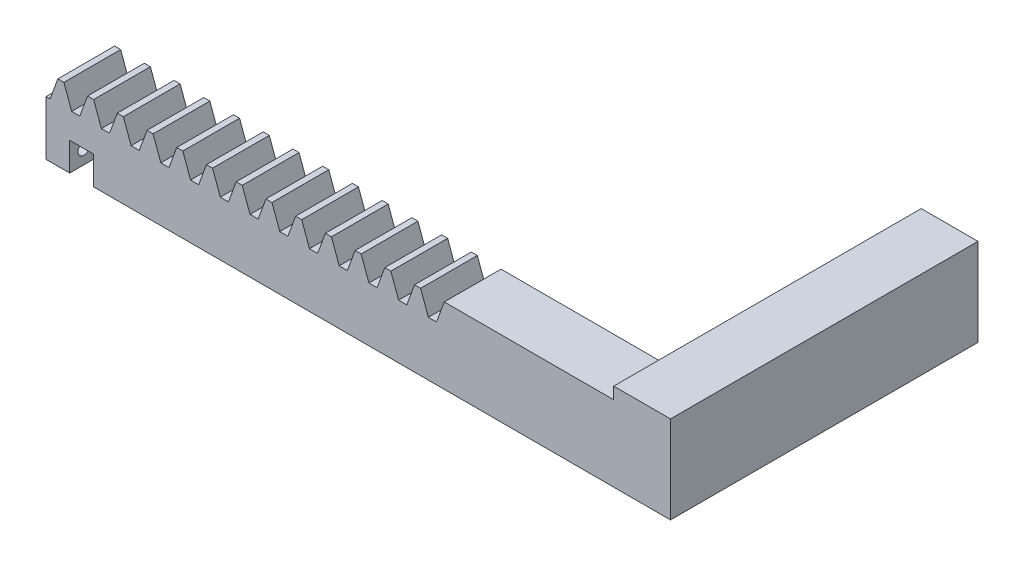
SolidWorks part; units mm, degrees
material "PLA"
ref_plane "Alzado" through (0, 0, 0) normal (0, 0, 1) x (1, 0, 0)
ref_plane "Planta" through (0, 0, 0) normal (0, 1, 0) x (1, 0, 0)
ref_plane "Vista lateral" through (0, 0, 0) normal (1, 0, 0) x (0, 0, -1)
ref_plane "Plane1" through (0, 0, -6) normal (0, 0, -1) x (-1, 0, 0)
sketch "Sketch1" plane through (0, 0, -6) normal (0, 0, -1) x (-1, 0, 0)
  line L0 (-70.7361, 14.6346) -> (-72.374, 10.1346)
  line L1 (-72.374, 10.1346) -> (-73.8553, 10.1346)
  line L2 (-73.8553, 10.1346) -> (-73.8553, -1.3654)
  line L3 (-73.8553, -1.3654) -> (46.1447, -1.3654)
  line L4 (46.1447, -1.3654) -> (46.1447, 10.1346)
  line L5 (46.1447, 10.1346) -> (45.2828, 10.1346)
  line L6 (45.2828, 10.1346) -> (43.6449, 14.6346)
  line L7 (43.6449, 14.6346) -> (42.3612, 14.6346)
  line L8 (42.3612, 14.6346) -> (40.7233, 10.1346)
  line L9 (40.7233, 10.1346) -> (38.9996, 10.1346)
  line L10 (38.9996, 10.1346) -> (37.3617, 14.6346)
  line L11 (37.3617, 14.6346) -> (36.078, 14.6346)
  line L12 (36.078, 14.6346) -> (34.4402, 10.1346)
  line L13 (34.4402, 10.1346) -> (32.7164, 10.1346)
  line L14 (32.7164, 10.1346) -> (31.0785, 14.6346)
  line L15 (31.0785, 14.6346) -> (29.7948, 14.6346)
  line L16 (29.7948, 14.6346) -> (28.157, 10.1346)
  line L17 (28.157, 10.1346) -> (26.4332, 10.1346)
  line L18 (26.4332, 10.1346) -> (24.7954, 14.6346)
  line L19 (24.7954, 14.6346) -> (23.5116, 14.6346)
  line L20 (23.5116, 14.6346) -> (21.8738, 10.1346)
  line L21 (21.8738, 10.1346) -> (20.15, 10.1346)
  line L22 (20.15, 10.1346) -> (18.5122, 14.6346)
  line L23 (18.5122, 14.6346) -> (17.2285, 14.6346)
  line L24 (17.2285, 14.6346) -> (15.5906, 10.1346)
  line L25 (15.5906, 10.1346) -> (13.8669, 10.1346)
  line L26 (13.8669, 10.1346) -> (12.229, 14.6346)
  line L27 (12.229, 14.6346) -> (10.9453, 14.6346)
  line L28 (10.9453, 14.6346) -> (9.3074, 10.1346)
  line L29 (9.3074, 10.1346) -> (7.5837, 10.1346)
  line L30 (7.5837, 10.1346) -> (5.9458, 14.6346)
  line L31 (5.9458, 14.6346) -> (4.6621, 14.6346)
  line L32 (4.6621, 14.6346) -> (3.0242, 10.1346)
  line L33 (3.0242, 10.1346) -> (1.3005, 10.1346)
  line L34 (1.3005, 10.1346) -> (-0.3374, 14.6346)
  line L35 (-0.3374, 14.6346) -> (-1.6211, 14.6346)
  line L36 (-1.6211, 14.6346) -> (-3.259, 10.1346)
  line L37 (-3.259, 10.1346) -> (-4.9827, 10.1346)
  line L38 (-4.9827, 10.1346) -> (-6.6206, 14.6346)
  line L39 (-6.6206, 14.6346) -> (-7.9043, 14.6346)
  line L40 (-7.9043, 14.6346) -> (-9.5421, 10.1346)
  line L41 (-9.5421, 10.1346) -> (-11.2659, 10.1346)
  line L42 (-11.2659, 10.1346) -> (-12.9038, 14.6346)
  line L43 (-12.9038, 14.6346) -> (-14.1875, 14.6346)
  line L44 (-14.1875, 14.6346) -> (-15.8253, 10.1346)
  line L45 (-15.8253, 10.1346) -> (-17.5491, 10.1346)
  line L46 (-17.5491, 10.1346) -> (-19.1869, 14.6346)
  line L47 (-19.1869, 14.6346) -> (-20.4707, 14.6346)
  line L48 (-20.4707, 14.6346) -> (-22.1085, 10.1346)
  line L49 (-22.1085, 10.1346) -> (-23.8323, 10.1346)
  line L50 (-23.8323, 10.1346) -> (-25.4701, 14.6346)
  line L51 (-25.4701, 14.6346) -> (-26.7538, 14.6346)
  line L52 (-26.7538, 14.6346) -> (-28.3917, 10.1346)
  line L53 (-28.3917, 10.1346) -> (-30.1154, 10.1346)
  line L54 (-30.1154, 10.1346) -> (-31.7533, 14.6346)
  line L55 (-31.7533, 14.6346) -> (-33.037, 14.6346)
  line L56 (-33.037, 14.6346) -> (-34.6749, 10.1346)
  line L57 (-34.6749, 10.1346) -> (-36.3986, 10.1346)
  line L58 (-36.3986, 10.1346) -> (-38.0365, 14.6346)
  line L59 (-38.0365, 14.6346) -> (-39.3202, 14.6346)
  line L60 (-39.3202, 14.6346) -> (-40.9581, 10.1346)
  line L61 (-40.9581, 10.1346) -> (-42.6818, 10.1346)
  line L62 (-42.6818, 10.1346) -> (-44.3197, 14.6346)
  line L63 (-44.3197, 14.6346) -> (-45.6034, 14.6346)
  line L64 (-45.6034, 14.6346) -> (-47.2413, 10.1346)
  line L65 (-47.2413, 10.1346) -> (-48.965, 10.1346)
  line L66 (-48.965, 10.1346) -> (-50.6029, 14.6346)
  line L67 (-50.6029, 14.6346) -> (-51.8866, 14.6346)
  line L68 (-51.8866, 14.6346) -> (-53.5244, 10.1346)
  line L69 (-53.5244, 10.1346) -> (-55.2482, 10.1346)
  line L70 (-55.2482, 10.1346) -> (-56.8861, 14.6346)
  line L71 (-56.8861, 14.6346) -> (-58.1698, 14.6346)
  line L72 (-58.1698, 14.6346) -> (-59.8076, 10.1346)
  line L73 (-59.8076, 10.1346) -> (-61.5314, 10.1346)
  line L74 (-61.5314, 10.1346) -> (-63.1692, 14.6346)
  line L75 (-63.1692, 14.6346) -> (-64.4529, 14.6346)
  line L76 (-64.4529, 14.6346) -> (-66.0908, 10.1346)
  line L77 (-66.0908, 10.1346) -> (-67.8146, 10.1346)
  line L78 (-67.8146, 10.1346) -> (-69.4524, 14.6346)
  line L79 (-69.4524, 14.6346) -> (-70.7361, 14.6346)
extrude "Boss-Extrude1" add sketch "Sketch1" against normal blind 12
sketch "Sketch2" plane through (0, -1.3654, 0) normal (0, -1, 0) x (1, 0, 0)
  line L0 (73.8553, 6) -> (-46.1447, 6) construction
  line L1 (-34.1447, 6) -> (-46.1447, 6)
  line L2 (-34.1447, 6) -> (-34.1447, -6)
  line L3 (-34.1447, -6) -> (-46.1447, -6)
  line L4 (-46.1447, 6) -> (-46.1447, -6)
  dimension "D1" = 12
extrude "Boss-Extrude2" [suppressed] add sketch "Sketch2" along normal blind 10
sketch "Sketch6" plane through (0, 0, 6) normal (0, 0, 1) x (1, 0, 0)
  line L1 (73.8553, 10.1346) -> (85.8553, 10.1346)
  line L2 (73.8553, 10.1346) -> (73.8553, -1.3654)
  line L3 (73.8553, -1.3654) -> (85.8553, -1.3654)
  line L4 (85.8553, 10.1346) -> (85.8553, -1.3654)
  dimension "D1" = 12
extrude "Boss-Extrude4" add sketch "Sketch6" against normal blind 65
sketch "Sketch7" plane through (0, 0, 6) normal (0, 0, 1) x (1, 0, 0)
  line L1 (73.8553, 10.1346) -> (85.8553, 10.1346)
  line L2 (73.8553, 10.1346) -> (73.8553, 17.1346)
  line L3 (73.8553, 17.1346) -> (85.8553, 17.1346)
  line L4 (85.8553, 10.1346) -> (85.8553, 17.1346)
  dimension "D1" = 7
  dimension "D2" = 12
extrude "Boss-Extrude5" add sketch "Sketch7" against normal blind 65
sketch "Sketch8" plane through (0, 0, 6) normal (0, 0, 1) x (1, 0, 0)
  line L0 (-41.1447, -1.3654) -> (-41.1447, 4.6346)
  line L1 (85.8553, -1.3654) -> (-46.1447, -1.3654) construction
  line L2 (-41.1447, 4.6346) -> (-36.1447, 4.6346)
  line L3 (-36.1447, 4.6346) -> (-36.1447, -1.3654)
  line L4 (-36.1447, -1.3654) -> (-31.1447, -1.3654)
  line L5 (-31.1447, -1.3654) -> (-31.1447, 4.259)
  line L6 (-46.1447, 4.6346) -> (-31.1447, 4.6346)
  line L7 (-31.1447, 4.6346) -> (-31.1447, 4.259)
  line L8 (-46.1447, -1.3654) -> (-46.1447, 10.1346) construction
  line L9 (-46.1447, 4.6346) -> (-46.1447, -1.3654)
  line L10 (-46.1447, -1.3654) -> (-41.1447, -1.3654)
  line L11 (-41.1447, -1.3654) -> (-36.1447, -1.3654)
  dimension "D1" = 5
  dimension "D2" = 5
  dimension "D3" = 5
  dimension "D4" = 6
  dimension "D5" = 6
extrude "Cut-Extrude1" cut sketch "Sketch8" against normal blind 65 contours L0 L11 L3 L2
sketch "Sketch9" plane through (0, 0, 6) normal (0, 0, 1) x (1, 0, 0)
  line L0 (73.8553, 17.1346) -> (73.8553, 10.1346) construction
  line L1 (73.8553, 14.6346) -> (38.9345, 14.6346)
  line L2 (73.8553, 14.6346) -> (73.8553, 10.1346)
  line L3 (73.8553, 10.1346) -> (38.9345, 10.1346)
  line L4 (38.9345, 14.6346) -> (38.9345, 10.1346)
extrude "Boss-Extrude6" add sketch "Sketch9" against normal blind 12
sketch "Sketch10" plane through (-46.1447, 0, 0) normal (-1, 0, 0) x (0, 0, 1)
  line L1 (6, -1.3654) -> (6, 10.1346) construction
  line L2 (6, -1.3654) -> (-6, -1.3654) construction
  circle A0 centre (-3, 1.6346) radius 1.25
  circle A1 centre (3, 1.6346) radius 1.25
  dimension "D1" = 3
  dimension "D5" = 2.5
  dimension "D6" = 2.5
  dimension "D2" = 3
  dimension "D3" = 9
  dimension "D4" = 3
extrude "Cut-Extrude2" cut sketch "Sketch10" against normal blind 12
